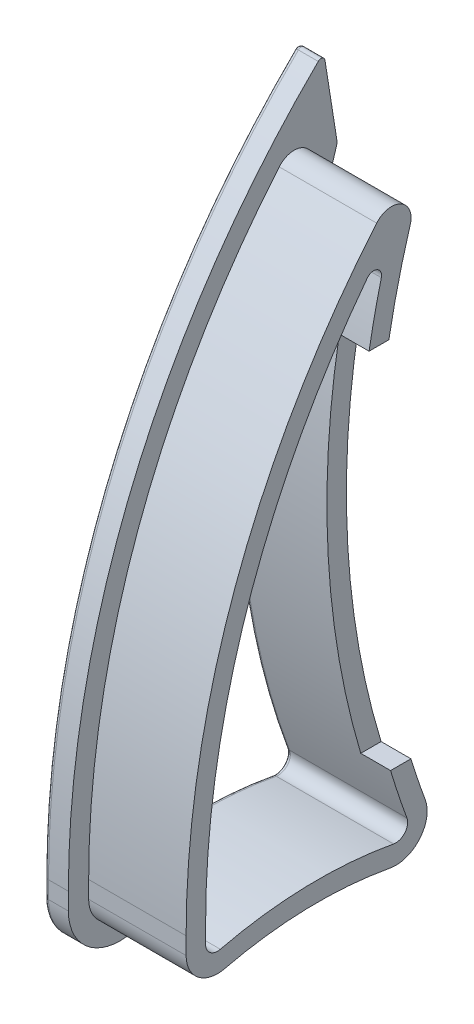
SolidWorks part; units mm, degrees
material "ABS"
ref_plane "Front Plane" through (0, 0, 0) normal (0, 0, 1) x (1, 0, 0)
ref_plane "Top Plane" through (0, 0, 0) normal (0, 1, 0) x (1, 0, 0)
ref_plane "Right Plane" through (0, 0, 0) normal (1, 0, 0) x (0, 0, -1)
sketch "Sketch1" plane through (0, 0, 0) normal (1, 0, 0) x (0, 0, -1)
  line L0 (-8.89, 10.8516) -> (-8.89, 9.7564)
  line L1 (0, 0) -> (0, 8.4759) construction
  arc A0 (3.2842, 44.1965) -> (-8.89, 10.8516) centre (42.8625, 10.8516) ccw
  arc A1 (5.4713, 43.0113) -> (3.2842, 44.1965) centre (4.2555, 43.3782) ccw
  arc A2 (5.4713, 43.0113) -> (6.4278, 10.7568) centre (54.1734, 28.3141) ccw
  arc A3 (4.1515, 8.0574) -> (6.4278, 10.7568) centre (4.5206, 10.0555) ccw
  arc A4 (4.1515, 8.0574) -> (-6.3843, 7.7804) centre (-0.4634, -16.9199) ccw
  arc A5 (-8.89, 9.7564) -> (-6.3843, 7.7804) centre (-6.858, 9.7564) ccw
sketch "Sketch2" plane through (0, 0, 0) normal (1, 0, 0) x (0, 0, -1)
  line L0 (-10.16, 10.8516) -> (-10.16, 9.7564)
  arc A12 (6.6872, 42.6444) -> (2.313, 45.0148) centre (4.2555, 43.3782) ccw
  arc A13 (-10.16, 9.7564) -> (-6.0883, 6.5453) centre (-6.858, 9.7564) ccw
  arc A14 (3.9207, 6.8085) -> (7.6198, 11.1952) centre (4.5206, 10.0555) ccw
  arc A15 (3.9207, 6.8085) -> (-6.0883, 6.5453) centre (-0.4634, -16.9199) ccw
  arc A16 (6.6872, 42.6444) -> (7.6198, 11.1952) centre (54.1734, 28.3141) ccw
  arc A17 (2.313, 45.0148) -> (-10.16, 10.8516) centre (42.8625, 10.8516) ccw
  arc A18 (6.6872, 42.6444) -> (2.313, 45.0148) centre (4.2555, 43.3782) ccw
  arc A19 (-10.16, 9.7564) -> (-6.0883, 6.5453) centre (-6.858, 9.7564) ccw
  arc A20 (3.9207, 6.8085) -> (7.6198, 11.1952) centre (4.5206, 10.0555) ccw
  arc A21 (3.9207, 6.8085) -> (-6.0883, 6.5453) centre (-0.4634, -16.9199) ccw
  arc A22 (6.6872, 42.6444) -> (7.6198, 11.1952) centre (54.1734, 28.3141) ccw
  arc A23 (2.313, 45.0148) -> (-10.16, 10.8516) centre (42.8625, 10.8516) ccw
  dimension "D1" = 1.27
extrude "Boss-Extrude1" add sketch "Sketch2" along normal blind 1.524
sketch "Sketch3" plane through (1.524, 0, 0) normal (1, 0, 0) x (0, 0, -1)
  line L2 (-7.62, 10.8516) -> (-7.62, 9.7564)
  line L3 (-7.62, 10.8516) -> (-7.62, 9.7564)
  arc A12 (4.2555, 43.3782) -> (5.2358, 10.3185) centre (54.1734, 28.3141) ccw
  arc A14 (4.2555, 43.3782) -> (-7.62, 10.8516) centre (42.8625, 10.8516) ccw
  arc A15 (-7.62, 9.7564) -> (-6.6804, 9.0154) centre (-6.858, 9.7564) ccw
  arc A16 (4.3822, 9.3062) -> (-6.6804, 9.0154) centre (-0.4634, -16.9199) ccw
  arc A17 (4.3822, 9.3062) -> (5.2358, 10.3185) centre (4.5206, 10.0555) ccw
  arc A18 (4.2555, 43.3782) -> (5.2358, 10.3185) centre (54.1734, 28.3141) ccw
  arc A20 (4.2555, 43.3782) -> (-7.62, 10.8516) centre (42.8625, 10.8516) ccw
  arc A21 (-7.62, 9.7564) -> (-6.6804, 9.0154) centre (-6.858, 9.7564) ccw
  arc A22 (4.3822, 9.3062) -> (-6.6804, 9.0154) centre (-0.4634, -16.9199) ccw
  arc A23 (4.3822, 9.3062) -> (5.2358, 10.3185) centre (4.5206, 10.0555) ccw
  dimension "D1" = 2.54
extrude "Cut-Extrude1" cut sketch "Sketch3" against normal up to surface (1.524 mm away) up to face at (0, 19.1554, 1.4286)
fillet "Fillet1" radius 0.508 1 edges at (0.762, 43.3782, -4.2555)
sketch "Sketch4" plane through (0, 0, 0) normal (-1, 0, 0) x (0, 0, 1)
  line L0 (7.62, 9.7564) -> (7.62, 10.8516) construction
  line L1 (7.62, 9.7564) -> (7.62, 10.8516)
  line L3 (8.89, 9.7564) -> (8.89, 10.8516)
  line L4 (8.89, 9.7564) -> (8.89, 10.8516)
  arc A0 (-5.2358, 10.3185) -> (-4.3822, 9.3062) centre (-4.5206, 10.0555) ccw construction
  arc A1 (6.6804, 9.0154) -> (-4.3822, 9.3062) centre (0.4634, -16.9199) ccw construction
  arc A2 (6.6804, 9.0154) -> (7.62, 9.7564) centre (6.858, 9.7564) ccw construction
  arc A3 (7.62, 10.8516) -> (-2.7049, 41.4432) centre (-42.8625, 10.8516) ccw construction
  arc A4 (-2.7049, 41.4432) -> (-3.6017, 41.0117) centre (-3.109, 41.1354) ccw construction
  arc A5 (-5.2358, 10.3185) -> (-3.6017, 41.0117) centre (-54.1734, 28.3141) ccw construction
  arc A6 (-5.2358, 10.3185) -> (-4.3822, 9.3062) centre (-4.5206, 10.0555) ccw
  arc A7 (6.6804, 9.0154) -> (-4.3822, 9.3062) centre (0.4634, -16.9199) ccw
  arc A8 (6.6804, 9.0154) -> (7.62, 9.7564) centre (6.858, 9.7564) ccw
  arc A9 (7.62, 10.8516) -> (-2.7049, 41.4432) centre (-42.8625, 10.8516) ccw
  arc A10 (-2.7049, 41.4432) -> (-3.6017, 41.0117) centre (-3.109, 41.1354) ccw
  arc A11 (-5.2358, 10.3185) -> (-3.6017, 41.0117) centre (-54.1734, 28.3141) ccw
  arc A18 (6.3843, 7.7804) -> (8.89, 9.7564) centre (6.858, 9.7564) ccw
  arc A19 (6.3843, 7.7804) -> (-4.1515, 8.0574) centre (0.4634, -16.9199) ccw
  arc A20 (-6.4278, 10.7568) -> (-4.1515, 8.0574) centre (-4.5206, 10.0555) ccw
  arc A21 (-6.4278, 10.7568) -> (-5.4713, 43.0113) centre (-54.1734, 28.3141) ccw
  arc A22 (-3.2842, 44.1965) -> (-5.4713, 43.0113) centre (-4.2555, 43.3782) ccw
  arc A23 (8.89, 10.8516) -> (-3.2842, 44.1965) centre (-42.8625, 10.8516) ccw
  arc A24 (6.3843, 7.7804) -> (8.89, 9.7564) centre (6.858, 9.7564) ccw
  arc A25 (6.3843, 7.7804) -> (-4.1515, 8.0574) centre (0.4634, -16.9199) ccw
  arc A26 (-6.4278, 10.7568) -> (-4.1515, 8.0574) centre (-4.5206, 10.0555) ccw
  arc A27 (-6.4278, 10.7568) -> (-5.4713, 43.0113) centre (-54.1734, 28.3141) ccw
  arc A28 (-3.2842, 44.1965) -> (-5.4713, 43.0113) centre (-4.2555, 43.3782) ccw
  arc A29 (8.89, 10.8516) -> (-3.2842, 44.1965) centre (-42.8625, 10.8516) ccw
  dimension "D1" = 0
extrude "Boss-Extrude2" add sketch "Sketch4" along normal blind 6.223
sketch "Sketch5" plane through (1.524, 0, 0) normal (1, 0, 0) x (0, 0, -1)
  line L0 (7.0091, 43.6708) -> (6.1482, 49.1066)
  line L1 (7.0091, 43.6708) -> (1.2178, 43.6708) construction
  line L2 (1.2178, 43.6708) -> (6.5347, 42.1289)
  arc A0 (6.6872, 42.6444) -> (7.6198, 11.1952) centre (54.1734, 28.3141) ccw construction
  arc A1 (7.0091, 43.6708) -> (6.5347, 42.1289) centre (54.1734, 28.3141) ccw
  arc A2 (2.313, 45.0148) -> (-10.16, 10.8516) centre (42.8625, 10.8516) ccw construction
  arc A3 (6.1482, 49.1066) -> (1.2178, 43.6708) centre (42.8625, 10.8516) ccw
  dimension "D1" = 81
extrude "Boss-Extrude3" add sketch "Sketch5" against normal up to surface (1.524 mm away) up to face at (0, 19.1554, 1.4286)
sketch "Sketch6" plane through (-6.223, 0, 0) normal (-1, 0, 0) x (0, 0, 1)
  line L1 (8.89, 9.7564) -> (8.89, 10.8516)
  line L2 (8.89, 9.7564) -> (8.89, 10.8516)
  line L4 (8.8646, 9.7564) -> (8.8646, 10.8516)
  line L5 (8.8646, 9.7564) -> (8.8646, 10.8516)
  arc A6 (8.89, 10.8516) -> (-3.2842, 44.1965) centre (-42.8625, 10.8516) ccw
  arc A7 (-3.2842, 44.1965) -> (-5.4713, 43.0113) centre (-4.2555, 43.3782) ccw
  arc A8 (-6.4278, 10.7568) -> (-5.4713, 43.0113) centre (-54.1734, 28.3141) ccw
  arc A9 (-6.4278, 10.7568) -> (-4.1515, 8.0574) centre (-4.5206, 10.0555) ccw
  arc A10 (6.3843, 7.7804) -> (-4.1515, 8.0574) centre (0.4634, -16.9199) ccw
  arc A11 (6.3843, 7.7804) -> (8.89, 9.7564) centre (6.858, 9.7564) ccw
  arc A12 (8.89, 10.8516) -> (-3.2842, 44.1965) centre (-42.8625, 10.8516) ccw
  arc A13 (-3.2842, 44.1965) -> (-5.4713, 43.0113) centre (-4.2555, 43.3782) ccw
  arc A14 (-6.4278, 10.7568) -> (-5.4713, 43.0113) centre (-54.1734, 28.3141) ccw
  arc A15 (-6.4278, 10.7568) -> (-4.1515, 8.0574) centre (-4.5206, 10.0555) ccw
  arc A16 (6.3843, 7.7804) -> (-4.1515, 8.0574) centre (0.4634, -16.9199) ccw
  arc A17 (6.3843, 7.7804) -> (8.89, 9.7564) centre (6.858, 9.7564) ccw
  arc A24 (8.8646, 10.8516) -> (-3.3037, 44.1801) centre (-42.8625, 10.8516) ccw
  arc A25 (-3.3037, 44.1801) -> (-5.447, 43.0186) centre (-4.2555, 43.3782) ccw
  arc A26 (-6.404, 10.7481) -> (-5.447, 43.0186) centre (-54.1734, 28.3141) ccw
  arc A27 (-6.404, 10.7481) -> (-4.1561, 8.0823) centre (-4.5206, 10.0555) ccw
  arc A28 (6.3902, 7.8051) -> (-4.1561, 8.0823) centre (0.4634, -16.9199) ccw
  arc A29 (6.3902, 7.8051) -> (8.8646, 9.7564) centre (6.858, 9.7564) ccw
  arc A30 (8.8646, 10.8516) -> (-3.3037, 44.1801) centre (-42.8625, 10.8516) ccw
  arc A31 (-3.3037, 44.1801) -> (-5.447, 43.0186) centre (-4.2555, 43.3782) ccw
  arc A32 (-6.404, 10.7481) -> (-5.447, 43.0186) centre (-54.1734, 28.3141) ccw
  arc A33 (-6.404, 10.7481) -> (-4.1561, 8.0823) centre (-4.5206, 10.0555) ccw
  arc A34 (6.3902, 7.8051) -> (-4.1561, 8.0823) centre (0.4634, -16.9199) ccw
  arc A35 (6.3902, 7.8051) -> (8.8646, 9.7564) centre (6.858, 9.7564) ccw
  dimension "D1" = 0
  dimension "D2" = 0.0254
extrude "Cut-Extrude2" cut sketch "Sketch6" against normal up to surface (6.223 mm away) up to face at (0, 19.369, 1.3756)
fillet "Fillet2" radius 0.254 1 edges at (0.762, 49.1066, -6.1482)
ref_plane "Plane1" through (0, 0, 12.7) normal (0, 0, 1) x (1, 0, 0)
ref_plane "Plane2" through (0, 0, -1.27) normal (0, 0, 1) x (1, 0, 0)
sketch "Sketch9" plane through (0, 0, -1.27) normal (0, 0, 1) x (1, 0, 0)
  line L0 (-6.223, 43.0186) -> (-6.223, 10.7481) construction
  line L1 (-6.223, 13.462) -> (-4.318, 13.462)
  line L2 (-6.223, 13.462) -> (-6.223, 37.338)
  line L3 (-6.223, 37.338) -> (-4.318, 37.338)
  line L4 (-4.318, 13.462) -> (-4.318, 37.338)
  dimension "D1" = 1.905
  dimension "D2" = 13.462
  dimension "D3" = 37.338
extrude "Cut-Extrude4" cut sketch "Sketch9" against normal through all
fillet "Fillet3" radius 0.254 15 edges at (1.524, 9.1581, 7.3299) (1.524, 10.304, 7.62) (1.524, 26.9951, 4.9692) (1.524, 41.5932, -3.3293) (1.524, 25.542, -2.1057) (1.524, 9.5643, -5.1032) (1.524, 46.1473, -6.6169) (1.524, 48.8251, -6.0536) (1.524, 31.419, 6.0084) (1.524, 10.304, 10.16) (1.524, 27.3816, -4.5808) (1.524, 7.9269, -7.045) (1.524, 7.2018, 1.0976) (1.524, 9.7409, 1.1643) (1.524, 7.1636, 8.9027)
mirror "Mirror2" about plane through (-6.223, 10.8516, -42.8625) normal (-1, 0, 0) of bodies 107
delete or keep bodies "Body-Delete/Keep 2" type delete bodies bodies 107
